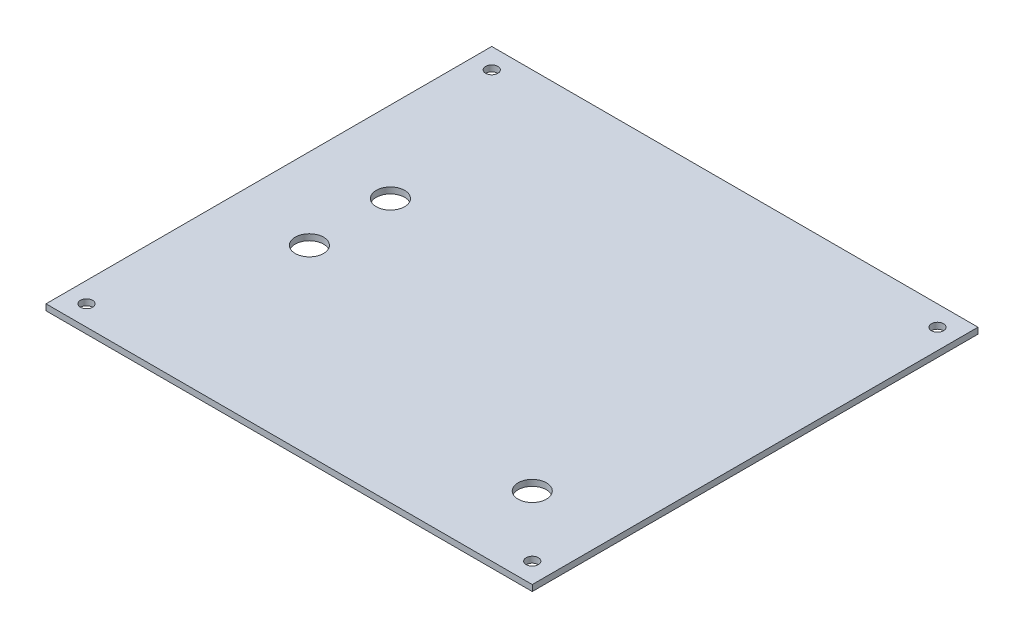
SolidWorks part; units mm, degrees
ref_plane "Front Plane" through (0, 0, 0) normal (0, 0, 1) x (1, 0, 0)
ref_plane "Top Plane" through (0, 0, 0) normal (0, 1, 0) x (1, 0, 0)
ref_plane "Right Plane" through (0, 0, 0) normal (1, 0, 0) x (0, 0, -1)
sketch "Sketch1" plane through (0, 0, 0) normal (0, 1, 0) x (1, 0, 0)
  line L0 (0, 55) -> (120, 55) construction
  line L1 (0, 0) -> (120, 0)
  line L2 (0, 0) -> (0, 110)
  line L3 (0, 110) -> (120, 110)
  line L4 (120, 0) -> (120, 110)
  circle A0 centre (5, 105) radius 1.5
  circle A1 centre (115, 105) radius 1.5
  circle A2 centre (115, 5) radius 1.5
  circle A3 centre (5, 5) radius 1.5
  circle A4 centre (100, 20) radius 3.5
  circle A5 centre (20, 65) radius 3.5
  circle A6 centre (20, 45) radius 3.5
  dimension "D3" = 3
  dimension "D4" = 5
  dimension "D6" = 3
  dimension "D7" = 5
  dimension "D8" = 5
  dimension "D9" = 3
  dimension "D10" = 5
  dimension "D11" = 5
  dimension "D12" = 3
  dimension "D13" = 5
  dimension "D14" = 5
  dimension "D15" = 7
  dimension "D16" = 20
  dimension "D17" = 20
  dimension "D18" = 7
  dimension "D19" = 7
  dimension "D20" = 20
  dimension "D21" = 20
  dimension "D22" = 10
  dimension "D23" = 10
  dimension "D1" = 110
  dimension "D2" = 120
  dimension "D5" = 5
extrude "Boss-Extrude1" add sketch "Sketch1" along normal blind 1.5
